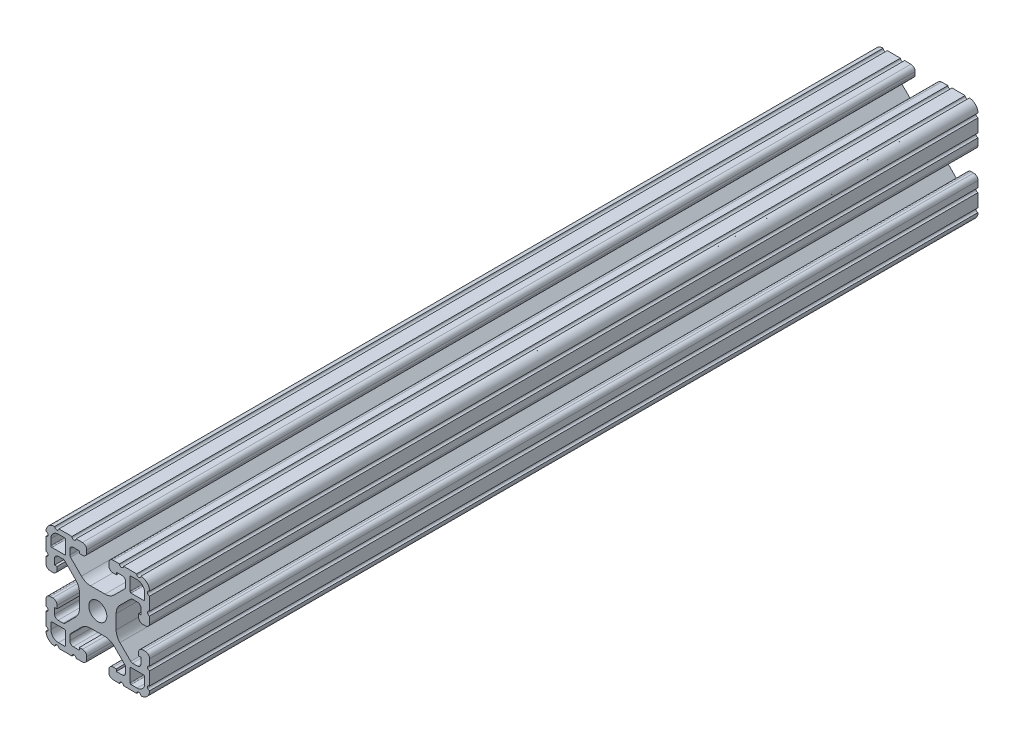
SolidWorks part; units mm, degrees
material "6061 Alloy"
ref_plane "Front Plane" through (0, 0, 0) normal (0, 0, 1) x (1, 0, 0)
ref_plane "Top Plane" through (0, 0, 0) normal (0, 1, 0) x (1, 0, 0)
ref_plane "Right Plane" through (0, 0, 0) normal (1, 0, 0) x (0, 0, -1)
sketch "Sketch1" plane through (0, 0, 0) normal (0, 0, 1) x (1, 0, 0)
  line L0 (0, 21.507) -> (0, -20.9529) construction
  line L1 (20.4424, 0) -> (-20.8151, 0) construction
  line L2 (10.0267, -12.1519) -> (6.0215, -8.1473)
  line L3 (-10.0267, 12.1519) -> (-6.0215, 8.1473)
  line L4 (-10.287, 14.5547) -> (-10.287, 12.7802)
  line L5 (-6.8141, 15.8247) -> (-9.017, 15.8247)
  line L6 (10.287, -14.5547) -> (10.287, -12.7802)
  line L7 (-6.8141, 14.986) -> (-6.8141, 15.8247)
  line L8 (6.8141, -15.8247) -> (9.017, -15.8247)
  line L9 (-2.6631, -6.7564) -> (2.6631, -6.7564)
  line L10 (6.8141, -14.986) -> (6.8141, -15.8247)
  line L11 (5.6388, -14.986) -> (6.8141, -14.986)
  line L12 (4.064, -17.4752) -> (4.064, -16.5608)
  line L13 (7.9756, -19.05) -> (5.6388, -19.05)
  line L14 (14.3256, -19.05) -> (9.4996, -19.05)
  line L15 (15.875, -19.05) -> (15.8496, -19.05)
  line L16 (19.05, -15.8496) -> (19.05, -15.875)
  line L17 (19.05, -9.4996) -> (19.05, -14.3256)
  line L18 (19.05, -5.6388) -> (19.05, -7.9756)
  line L19 (-5.6388, 14.986) -> (-6.8141, 14.986)
  line L20 (-4.064, 17.4752) -> (-4.064, 16.5608)
  line L21 (-7.9756, 19.05) -> (-5.6388, 19.05)
  line L22 (16.5608, -4.064) -> (17.4752, -4.064)
  line L23 (-14.3256, 19.05) -> (-9.4996, 19.05)
  line L24 (14.986, -6.7506) -> (14.986, -5.6388)
  line L25 (15.879, -6.7506) -> (14.986, -6.7506)
  line L26 (-15.875, 19.05) -> (-15.8496, 19.05)
  line L27 (-19.05, 15.8496) -> (-19.05, 15.875)
  line L28 (15.879, -8.9192) -> (15.879, -6.7506)
  line L29 (12.7428, -10.1892) -> (14.609, -10.1892)
  line L30 (-19.05, 9.4996) -> (-19.05, 14.3256)
  line L31 (-19.05, 5.6388) -> (-19.05, 7.9756)
  line L32 (8.1479, -5.9632) -> (12.1142, -9.9289)
  line L33 (16.891, -11.8618) -> (12.2428, -11.8618)
  line L34 (11.8618, -12.2428) -> (11.8618, -16.891)
  line L35 (12.2428, -17.272) -> (14.478, -17.272)
  line L36 (17.272, 14.478) -> (17.272, 12.2428)
  line L37 (12.2428, 17.272) -> (14.478, 17.272)
  line L38 (11.8618, 12.2428) -> (11.8618, 16.891)
  line L39 (16.891, 11.8618) -> (12.2428, 11.8618)
  line L40 (17.272, -14.478) -> (17.272, -12.2428)
  line L41 (-16.5608, 4.064) -> (-17.4752, 4.064)
  line L42 (-14.986, 6.7506) -> (-14.986, 5.6388)
  line L43 (-15.879, 6.7506) -> (-14.986, 6.7506)
  line L44 (-15.879, 8.9192) -> (-15.879, 6.7506)
  line L45 (-12.7428, 10.1892) -> (-14.609, 10.1892)
  line L46 (-8.1479, 5.9632) -> (-12.1142, 9.9289)
  line L47 (-6.7564, -2.6043) -> (-6.7564, 2.6043)
  line L48 (-17.272, -14.478) -> (-17.272, -12.2428)
  line L49 (-16.891, 11.8618) -> (-12.2428, 11.8618)
  line L50 (-11.8618, 12.2428) -> (-11.8618, 16.891)
  line L51 (-12.2428, 17.272) -> (-14.478, 17.272)
  line L52 (-17.272, 14.478) -> (-17.272, 12.2428)
  line L53 (-12.2428, -17.272) -> (-14.478, -17.272)
  line L54 (-11.8618, -12.2428) -> (-11.8618, -16.891)
  line L55 (-16.891, -11.8618) -> (-12.2428, -11.8618)
  line L56 (-8.1479, -5.9632) -> (-12.1142, -9.9289)
  line L57 (-12.7428, -10.1892) -> (-14.609, -10.1892)
  line L58 (-15.879, -8.9192) -> (-15.879, -6.7506)
  line L59 (-15.879, -6.7506) -> (-14.986, -6.7506)
  line L60 (-14.986, -6.7506) -> (-14.986, -5.6388)
  line L61 (-16.5608, -4.064) -> (-17.4752, -4.064)
  line L62 (-19.05, -5.6388) -> (-19.05, -7.9756)
  line L63 (-19.05, -9.4996) -> (-19.05, -14.3256)
  line L64 (-19.05, -15.8496) -> (-19.05, -15.875)
  line L65 (-15.875, -19.05) -> (-15.8496, -19.05)
  line L66 (-14.3256, -19.05) -> (-9.4996, -19.05)
  line L67 (-7.9756, -19.05) -> (-5.6388, -19.05)
  line L68 (-4.064, -17.4752) -> (-4.064, -16.5608)
  line L69 (-5.6388, -14.986) -> (-6.8141, -14.986)
  line L70 (-6.8141, -14.986) -> (-6.8141, -15.8247)
  line L71 (-6.8141, -15.8247) -> (-9.017, -15.8247)
  line L72 (-10.287, -14.5547) -> (-10.287, -12.7802)
  line L73 (-10.0267, -12.1519) -> (-6.0215, -8.1473)
  line L95 (6.7564, -2.6043) -> (6.7564, 2.6043)
  line L96 (8.1479, 5.9632) -> (12.1142, 9.9289)
  line L97 (12.7428, 10.1892) -> (14.609, 10.1892)
  line L98 (15.879, 8.9192) -> (15.879, 6.7506)
  line L99 (15.879, 6.7506) -> (14.986, 6.7506)
  line L100 (14.986, 6.7506) -> (14.986, 5.6388)
  line L101 (16.5608, 4.064) -> (17.4752, 4.064)
  line L102 (19.05, 5.6388) -> (19.05, 7.9756)
  line L103 (19.05, 9.4996) -> (19.05, 14.3256)
  line L104 (19.05, 15.8496) -> (19.05, 15.875)
  line L105 (15.875, 19.05) -> (15.8496, 19.05)
  line L106 (14.3256, 19.05) -> (9.4996, 19.05)
  line L107 (7.9756, 19.05) -> (5.6388, 19.05)
  line L108 (4.064, 17.4752) -> (4.064, 16.5608)
  line L109 (5.6388, 14.986) -> (6.8141, 14.986)
  line L110 (6.8141, 14.986) -> (6.8141, 15.8247)
  line L111 (6.8141, 15.8247) -> (9.017, 15.8247)
  line L112 (10.287, 14.5547) -> (10.287, 12.7802)
  line L113 (10.0267, 12.1519) -> (6.0215, 8.1473)
  line L114 (2.6631, 6.7564) -> (-2.6631, 6.7564)
  arc A0 (10.0267, -12.1519) -> (10.287, -12.7802) centre (9.3985, -12.7802) cw
  arc A1 (10.287, -14.5547) -> (9.017, -15.8247) centre (9.017, -14.5547) cw
  arc A2 (4.064, -16.5608) -> (5.6388, -14.986) centre (5.6388, -16.5608) cw
  arc A3 (-10.0267, 12.1519) -> (-10.287, 12.7802) centre (-9.3985, 12.7802) cw
  arc A4 (-10.287, 14.5547) -> (-9.017, 15.8247) centre (-9.017, 14.5547) cw
  arc A5 (5.6388, -19.05) -> (4.064, -17.4752) centre (5.6388, -17.4752) cw
  arc A6 (7.9756, -19.05) -> (9.4996, -19.05) centre (8.7376, -19.05) cw
  arc A7 (-4.064, 16.5608) -> (-5.6388, 14.986) centre (-5.6388, 16.5608) cw
  arc A8 (14.3256, -19.05) -> (15.8496, -19.05) centre (15.0876, -19.05) cw
  arc A9 (19.05, -15.875) -> (15.875, -19.05) centre (15.875, -15.875) cw
  arc A10 (6.0215, -8.1473) -> (2.6631, -6.7564) centre (2.6631, -11.5062) ccw
  arc A11 (-6.0215, -8.1473) -> (-2.6631, -6.7564) centre (-2.6631, -11.5062) cw
  arc A12 (19.05, -15.8496) -> (19.05, -14.3256) centre (19.05, -15.0876) cw
  arc A13 (19.05, -9.4996) -> (19.05, -7.9756) centre (19.05, -8.7376) cw
  arc A14 (17.4752, -4.064) -> (19.05, -5.6388) centre (17.4752, -5.6388) cw
  arc A15 (14.986, -5.6388) -> (16.5608, -4.064) centre (16.5608, -5.6388) cw
  arc A16 (15.879, -8.9192) -> (14.609, -10.1892) centre (14.609, -8.9192) cw
  arc A17 (12.7428, -10.1892) -> (12.1142, -9.9289) centre (12.7428, -9.3002) cw
  arc A18 (16.891, -11.8618) -> (17.272, -12.2428) centre (16.891, -12.2428) cw
  arc A19 (-5.6388, 19.05) -> (-4.064, 17.4752) centre (-5.6388, 17.4752) cw
  arc A20 (-7.9756, 19.05) -> (-9.4996, 19.05) centre (-8.7376, 19.05) cw
  arc A21 (-14.3256, 19.05) -> (-15.8496, 19.05) centre (-15.0876, 19.05) cw
  arc A22 (11.8618, -12.2428) -> (12.2428, -11.8618) centre (12.2428, -12.2428) cw
  arc A23 (-19.05, 15.875) -> (-15.875, 19.05) centre (-15.875, 15.875) cw
  arc A24 (12.2428, -17.272) -> (11.8618, -16.891) centre (12.2428, -16.891) cw
  arc A25 (17.272, -14.478) -> (14.478, -17.272) centre (14.478, -14.478) cw
  arc A26 (-19.05, 15.8496) -> (-19.05, 14.3256) centre (-19.05, 15.0876) cw
  arc A27 (-19.05, 9.4996) -> (-19.05, 7.9756) centre (-19.05, 8.7376) cw
  arc A28 (-17.4752, 4.064) -> (-19.05, 5.6388) centre (-17.4752, 5.6388) cw
  arc A29 (-14.986, 5.6388) -> (-16.5608, 4.064) centre (-16.5608, 5.6388) cw
  arc A30 (-15.879, 8.9192) -> (-14.609, 10.1892) centre (-14.609, 8.9192) cw
  arc A31 (-12.7428, 10.1892) -> (-12.1142, 9.9289) centre (-12.7428, 9.3002) cw
  arc A32 (-8.1479, 5.9632) -> (-6.7564, 2.6043) centre (-11.5062, 2.6043) cw
  arc A33 (-6.7564, -2.6043) -> (-8.1479, -5.9632) centre (-11.5062, -2.6043) cw
  arc A34 (-16.891, 11.8618) -> (-17.272, 12.2428) centre (-16.891, 12.2428) cw
  arc A35 (-11.8618, 12.2428) -> (-12.2428, 11.8618) centre (-12.2428, 12.2428) cw
  arc A36 (17.272, 14.478) -> (14.478, 17.272) centre (14.478, 14.478) ccw
  arc A37 (12.2428, 17.272) -> (11.8618, 16.891) centre (12.2428, 16.891) ccw
  arc A38 (11.8618, 12.2428) -> (12.2428, 11.8618) centre (12.2428, 12.2428) ccw
  arc A39 (16.891, 11.8618) -> (17.272, 12.2428) centre (16.891, 12.2428) ccw
  arc A40 (-12.2428, 17.272) -> (-11.8618, 16.891) centre (-12.2428, 16.891) cw
  circle A41 centre (0, 0) radius 3.3274
  arc A42 (-17.272, 14.478) -> (-14.478, 17.272) centre (-14.478, 14.478) cw
  arc A43 (-17.272, -14.478) -> (-14.478, -17.272) centre (-14.478, -14.478) ccw
  arc A44 (-12.2428, -17.272) -> (-11.8618, -16.891) centre (-12.2428, -16.891) ccw
  arc A45 (-11.8618, -12.2428) -> (-12.2428, -11.8618) centre (-12.2428, -12.2428) ccw
  arc A46 (-16.891, -11.8618) -> (-17.272, -12.2428) centre (-16.891, -12.2428) ccw
  arc A47 (-12.7428, -10.1892) -> (-12.1142, -9.9289) centre (-12.7428, -9.3002) ccw
  arc A48 (-15.879, -8.9192) -> (-14.609, -10.1892) centre (-14.609, -8.9192) ccw
  arc A49 (-14.986, -5.6388) -> (-16.5608, -4.064) centre (-16.5608, -5.6388) ccw
  arc A50 (-17.4752, -4.064) -> (-19.05, -5.6388) centre (-17.4752, -5.6388) ccw
  arc A51 (-19.05, -9.4996) -> (-19.05, -7.9756) centre (-19.05, -8.7376) ccw
  arc A52 (-19.05, -15.8496) -> (-19.05, -14.3256) centre (-19.05, -15.0876) ccw
  arc A53 (-19.05, -15.875) -> (-15.875, -19.05) centre (-15.875, -15.875) ccw
  arc A54 (-14.3256, -19.05) -> (-15.8496, -19.05) centre (-15.0876, -19.05) ccw
  arc A55 (-7.9756, -19.05) -> (-9.4996, -19.05) centre (-8.7376, -19.05) ccw
  arc A56 (-5.6388, -19.05) -> (-4.064, -17.4752) centre (-5.6388, -17.4752) ccw
  arc A57 (-4.064, -16.5608) -> (-5.6388, -14.986) centre (-5.6388, -16.5608) ccw
  arc A58 (-10.287, -14.5547) -> (-9.017, -15.8247) centre (-9.017, -14.5547) ccw
  arc A59 (-10.0267, -12.1519) -> (-10.287, -12.7802) centre (-9.3985, -12.7802) ccw
  arc A86 (6.7564, -2.6043) -> (8.1479, -5.9632) centre (11.5062, -2.6043) ccw
  arc A87 (8.1479, 5.9632) -> (6.7564, 2.6043) centre (11.5062, 2.6043) ccw
  arc A88 (12.7428, 10.1892) -> (12.1142, 9.9289) centre (12.7428, 9.3002) ccw
  arc A89 (15.879, 8.9192) -> (14.609, 10.1892) centre (14.609, 8.9192) ccw
  arc A90 (14.986, 5.6388) -> (16.5608, 4.064) centre (16.5608, 5.6388) ccw
  arc A91 (17.4752, 4.064) -> (19.05, 5.6388) centre (17.4752, 5.6388) ccw
  arc A92 (19.05, 9.4996) -> (19.05, 7.9756) centre (19.05, 8.7376) ccw
  arc A93 (19.05, 15.8496) -> (19.05, 14.3256) centre (19.05, 15.0876) ccw
  arc A94 (19.05, 15.875) -> (15.875, 19.05) centre (15.875, 15.875) ccw
  arc A95 (14.3256, 19.05) -> (15.8496, 19.05) centre (15.0876, 19.05) ccw
  arc A96 (7.9756, 19.05) -> (9.4996, 19.05) centre (8.7376, 19.05) ccw
  arc A97 (5.6388, 19.05) -> (4.064, 17.4752) centre (5.6388, 17.4752) ccw
  arc A98 (4.064, 16.5608) -> (5.6388, 14.986) centre (5.6388, 16.5608) ccw
  arc A99 (10.287, 14.5547) -> (9.017, 15.8247) centre (9.017, 14.5547) ccw
  arc A100 (10.0267, 12.1519) -> (10.287, 12.7802) centre (9.3985, 12.7802) ccw
  arc A101 (2.6631, 6.7564) -> (6.0215, 8.1473) centre (2.6631, 11.5062) ccw
  arc A102 (-6.0215, 8.1473) -> (-2.6631, 6.7564) centre (-2.6631, 11.5062) ccw
  dimension "D1" = 6.6548
  dimension "D2" = 38.1
  dimension "D3" = 20.574
  dimension "D4" = 12.2936
  dimension "D5" = 19.05
  dimension "D6" = 8.128
  dimension "D7" = 3.048
  dimension "D8" = 4.064
  dimension "D9" = 13.5128
extrude "Extrude1" add sketch "Sketch1" against normal blind 304.8
